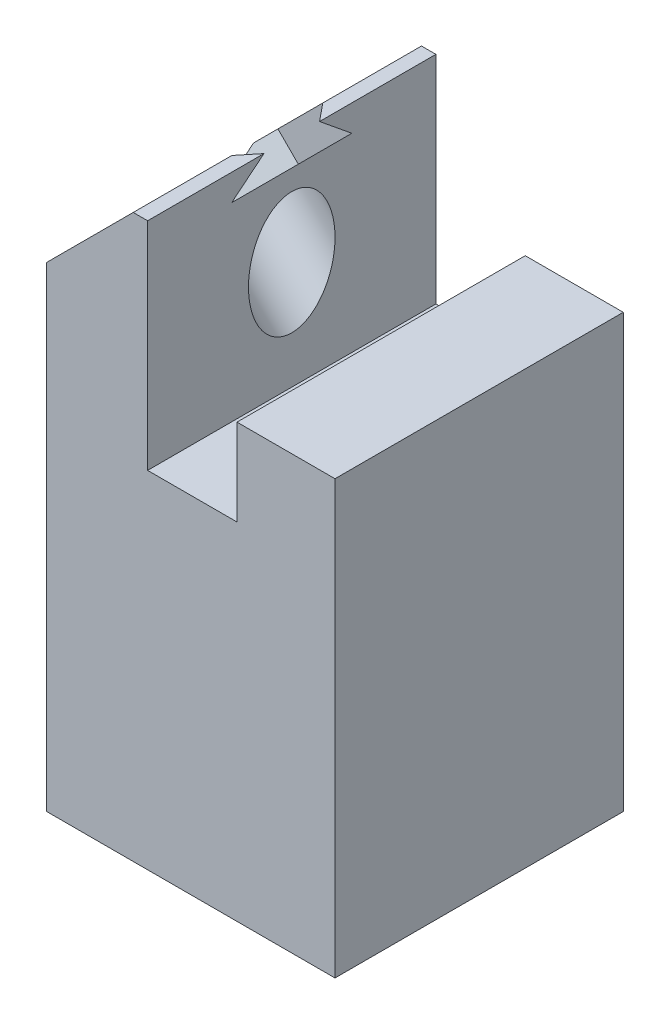
SolidWorks part; units mm, degrees
ref_plane "Front Plane" through (0, 0, 0) normal (0, 0, 1) x (1, 0, 0)
ref_plane "Top Plane" through (0, 0, 0) normal (0, 1, 0) x (1, 0, 0)
ref_plane "Right Plane" through (0, 0, 0) normal (1, 0, 0) x (0, 0, -1)
sketch "Sketch1" plane through (0, 0, 0) normal (0, 1, 0) x (1, 0, 0)
  line L1 (-10, -10) -> (10, -10)
  line L2 (-10, -10) -> (-10, 10)
  line L3 (-10, 10) -> (10, 10)
  line L4 (10, -10) -> (10, 10)
  line L5 (-10, -10) -> (10, 10) construction
  line L6 (-10, 10) -> (10, -10) construction
  point P0 (0, 0)
extrude "Boss-Extrude1" add sketch "Sketch1" along normal blind 6
sketch "Sketch2" plane through (0, 6, 0) normal (0, 1, 0) x (1, 0, 0)
  line L2 (-10, -10) -> (10, -10) construction
  line L3 (3.2, -10) -> (10, -10)
  line L4 (3.2, -10) -> (3.2, 10)
  line L5 (3.2, 10) -> (10, 10)
  line L6 (10, -10) -> (10, 10)
extrude "Boss-Extrude2" add sketch "Sketch2" along normal blind 6
sketch "Sketch3" plane through (0, 6, 0) normal (0, 1, 0) x (1, 0, 0)
  line L0 (-10, 0) -> (-3, 0) construction
  line L1 (-10, 10) -> (-10, -10) construction
  line L2 (3.2, 10) -> (-10, 10) construction
  line L3 (-10, -10) -> (-3, -10)
  line L4 (-10, -10) -> (-10, 10)
  line L5 (-10, 10) -> (-3, 10)
  line L6 (-3, -10) -> (-3, 10)
extrude "Boss-Extrude3" add sketch "Sketch3" along normal blind 15
chamfer "Chamfer1" distance 6 angle 45 1 edges at (-10, 21, 0)
sketch "Sketch4" plane through (-12.5, 12.5, 0) normal (-0.7071, 0.7071, 0) x (0, 0, 1)
  line L0 (0, 3.5355) -> (0, 5.4132) construction
  line L1 (10, 3.5355) -> (-10, 3.5355) construction
  line L2 (0, 5.4132) -> (0, 7.4325) construction
  circle A0 centre (0, 7.4325) radius 3
extrude "Cut-Extrude1" cut sketch "Sketch4" against normal blind 10 contours A0
sketch "Sketch5" plane through (0, 0, 0) normal (0, -1, 0) x (1, 0, 0)
  line L1 (10, -10) -> (-10, -10)
  line L2 (10, -10) -> (10, 10)
  line L3 (10, 10) -> (-10, 10)
  line L4 (-10, -10) -> (-10, 10)
  line L5 (10, -10) -> (-10, 10) construction
  line L6 (10, 10) -> (-10, -10) construction
  point P0 (0, 0)
extrude "Boss-Extrude4" add sketch "Sketch5" along normal blind 18
sketch "Sketch6" plane through (-12.5, 12.5, 0) normal (-0.7071, 0.7071, 0) x (0, 0, 1)
  line L1 (0, 13.8411) -> (-5.55, 10.6368)
  line L2 (-5.55, 10.6368) -> (-5.55, 4.2282)
  line L3 (-5.55, 4.2282) -> (0, 1.0239)
  line L4 (0, 1.0239) -> (5.55, 4.2282)
  line L5 (5.55, 4.2282) -> (5.55, 10.6368)
  line L6 (5.55, 10.6368) -> (0, 13.8411)
  circle A0 centre (0, 7.4325) radius 5.55 construction
extrude "Cut-Extrude2" cut sketch "Sketch6" against normal blind 2 contours L1 L2 L3 L4 L5 L6
sketch "Sketch7" plane through (0, -18, 0) normal (0, -1, 0) x (-1, 0, 0)
  circle A0 centre (0, 0) radius 2.8
extrude "Cut-Extrude3" cut sketch "Sketch7" against normal blind 20
sketch "Sketch8" plane through (0, -18, 0) normal (0, -1, 0) x (-1, 0, 0)
  line L1 (5.0386, -2.9352) -> (5.0613, 2.896)
  line L2 (5.0613, 2.896) -> (0.0227, 5.8312)
  line L3 (0.0227, 5.8312) -> (-5.0386, 2.9352)
  line L4 (-5.0386, 2.9352) -> (-5.0613, -2.896)
  line L5 (-5.0613, -2.896) -> (-0.0227, -5.8312)
  line L6 (-0.0227, -5.8312) -> (5.0386, -2.9352)
  circle A0 centre (0, 0) radius 5.05 construction
extrude "Cut-Extrude4" cut sketch "Sketch8" against normal blind 6
